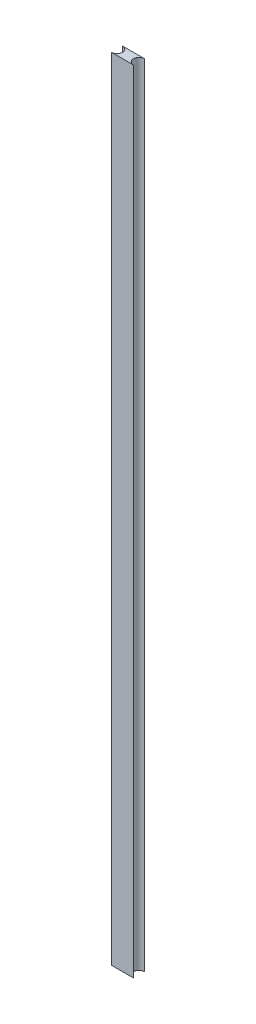
SolidWorks part; units mm, degrees
ref_plane "Front Plane" through (0, 0, 0) normal (0, 0, 1) x (1, 0, 0)
ref_plane "Top Plane" through (0, 0, 0) normal (0, 1, 0) x (1, 0, 0)
ref_plane "Right Plane" through (0, 0, 0) normal (1, 0, 0) x (0, 0, -1)
sketch "Sketch1" plane through (0, 0, 0) normal (0, 1, 0) x (1, 0, 0)
  line L1 (-44.5717, -191.6397) -> (5.4283, -191.6397)
  line L3 (-44.5717, -216.6397) -> (5.4283, -216.6397)
  arc A0 (-44.5717, -216.6397) -> (-44.5717, -191.6397) centre (-44.5717, -204.1397) ccw
  arc A1 (5.4283, -191.6397) -> (5.4283, -216.6397) centre (5.4283, -204.1397) ccw
  dimension "D2" = 25
extrude "Boss-Extrude1" add sketch "Sketch1" along normal blind 1800
